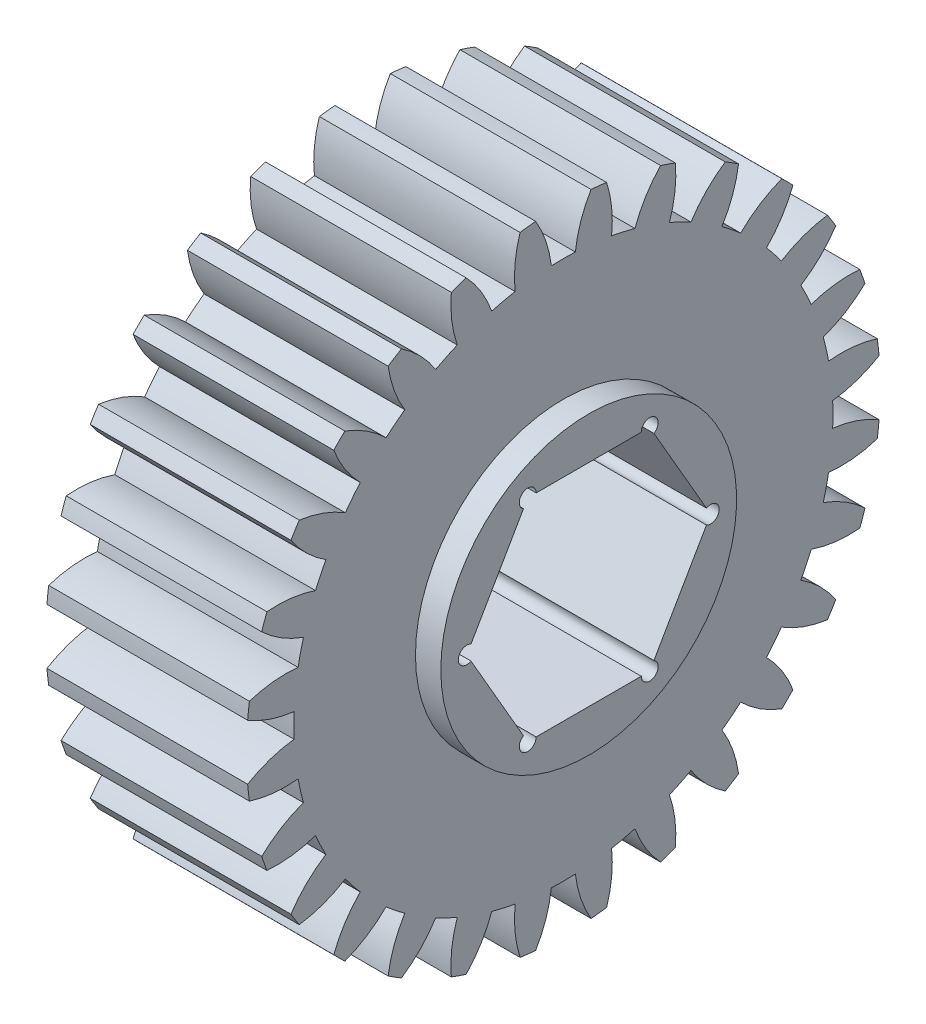
SolidWorks part; units mm, degrees
ref_plane "Plane1" through (0, 0, 0) normal (0, 0, 1) x (1, 0, 0)
ref_plane "Plane2" through (0, 0, 0) normal (0, 1, 0) x (1, 0, 0)
ref_plane "Plane3" through (0, 0, 0) normal (1, 0, 0) x (0, 0, -1)
sketch "HoldingSke" plane through (0, 0, 0) normal (0, 1, 0) x (1, 0, 0)
  line L0 (0, 0) -> (448.5374, -238.4916)
  line L1 (-15, 0) -> (100, 0) construction
  line L2 (0, 0) -> (-2.1039, 2.3779)
  line L3 (0, 0) -> (-11.863, 4.5341)
  line L4 (0, 0) -> (7.6251, 4.0544)
  line L5 (0, 0) -> (-47.5972, -17.7524)
  line L6 (0, 0) -> (-10.0014, -6.748)
  line L7 (-2.1039, 2.3779) -> (8.8308, 51.9871)
  line L8 (-76.2, 54.61) -> (-72.771, 54.61)
  line L9 (-67.7845, 28.3722) -> (-49.3413, 33.142)
  line L10 (-76.2, 71.12) -> (104.1128, 71.12)
  line L11 (0, 0) -> (-12.065, 0)
  line L12 (-76.2, 101.6) -> (-76.1492, 101.6)
  line L13 (24.9733, 27.94) -> (52.9518, 28.4284)
  line L14 (24.9733, 27.94) -> (25.0241, 27.9398)
  line L15 (24.9733, 27.94) -> (100.4021, 29.52)
  circle A0 centre (0, 0) radius 1.5875
  circle A1 centre (0, 0) radius 16.2052
  circle A2 centre (0, 0) radius 38.1
  circle A3 centre (0, 0) radius 1.5875
  dimension "MHD" = 32.4104
  dimension "Hub_dia" = 76.2
  dimension "Bore" = 3.175
  dimension "MBD" = 3.175
  dimension "Num_teeth" = 28
  dimension "Pitch" = 508
  dimension "Overall_len" = 50.8
  dimension "Show_teeth" = 28
  dimension "Thickness" = 12.065
  dimension "OAL" = 50.8001
  dimension "T_dim" = 3.429
  dimension "Ap" = 14.5
  dimension "H" = 19.05
  dimension "Pitch_radius" = 180.3128
  dimension "Width" = 12.065
  dimension "Backlash" = 0.0508
  dimension "Addendum_fac" = 1
  dimension "Dedendum_fac" = 1.2
  dimension "Clearance_fac" = 0.2
  dimension "Dedendum_add" = 0.0508
sketch "BasProSke" plane through (0, 0, 0) normal (0, 1, 0) x (1, 0, 0)
  line L0 (-10, 0) -> (60, 0) construction
  line L1 (0, 0) -> (0, 19.05)
  line L2 (0, 0) -> (12.065, 0)
  line L3 (12.065, 0) -> (12.065, 19.05)
  line L4 (12.065, 19.05) -> (0, 19.05)
  dimension "Thickness" = 12.065
  dimension "Diameter" = 38.1
revolve "Base-Revolve" add sketch "BasProSke" angle 360 about L0
sketch "TooCutSke" plane through (0, 0, 0) normal (1, 0, 0) x (0, 0, -1)
  line L1 (0, 0) -> (0, 107) construction
  line L2 (0, 0) -> (-1.0858, 17.7468) construction
  line L3 (0, 0) -> (-3.9763, 35.2903) construction
  line L4 (-1.0858, 17.7468) -> (-1.9881, 17.6451) construction
  arc A0 (0.7203, 16.1892) -> (-0.7203, 16.1892) centre (0, 0) ccw
  arc A1 (1.6778, 19.0015) -> (-1.6778, 19.0015) centre (0, 0) ccw
  circle A2 centre (0, 0) radius 17.78 construction
  circle A3 centre (0, 0) radius 17.2137 construction
  arc A4 (-0.7203, 16.1892) -> (-1.6778, 19.0015) centre (-7.7831, 15.3536) ccw
  arc A5 (1.6778, 19.0015) -> (0.7203, 16.1892) centre (7.7831, 15.3536) ccw
  dimension "Root_dia" = 32.4104
  dimension "Overcut_dia" = 38.1508
  dimension "Pitch_dia" = 35.56
  dimension "Base_dia" = 34.4273
  dimension "Flank_rad" = 7.112
  dimension "Half_ang" = 6.429
  dimension "Half_CT" = 0.908
extrude "ToothCut" cut sketch "TooCutSke" along normal through all
fillet "Breaks" [suppressed] radius 0.0254
fillet "RootFillets" [suppressed] radius 0.3048
pattern_circular "TeethCuts" count 28 every 12.857 about axis through (-10, 0, 0) along (1, 0, 0) of "ToothCut", "RootFillets", "Breaks"
sketch "HubNeaOneSke" plane through (0, 0, 0) normal (-1, 0, 0) x (0, 0, 1)
  circle A0 centre (0, 0) radius 16.2052
  dimension "Diameter" = 32.4104
extrude "HubNearOne" [suppressed] add sketch "HubNeaOneSke" along normal blind 38.7351
sketch "HubNeaBotSke" plane through (0, 0, 0) normal (-1, 0, 0) x (0, 0, 1)
  circle A0 centre (0, 0) radius 16.2052
  dimension "Diameter" = 32.4104
extrude "HubNearBoth" [suppressed] add sketch "HubNeaBotSke" along normal blind 19.3675
ref_plane "FarPln" through (12.065, 0, 0) normal (1, 0, 0) x (0, 0, -1)
sketch "HubFarSke" plane through (12.065, 0, 0) normal (1, 0, 0) x (0, 0, -1)
  circle A0 centre (0, 0) radius 16.2052
  dimension "Diameter" = 32.4104
extrude "HubFar" [suppressed] add sketch "HubFarSke" along normal blind 19.3675
sketch "BorSke" plane through (0, 0, 0) normal (1, 0, 0) x (0, 0, -1)
  circle A0 centre (0, 0) radius 1.5875
  dimension "Diameter" = 3.175
extrude "Bore" cut sketch "BorSke" along normal mid plane 101.6001
sketch "KeySke" plane through (0, 0, 0) normal (1, 0, 0) x (0, 0, -1)
  line L0 (-0.127, 0) -> (-0.127, 1.8415)
  line L1 (-0.127, 1.8415) -> (0.127, 1.8415)
  line L2 (0.127, 1.8415) -> (0.127, 0)
  line L3 (0, 0) -> (0, 34) construction
  line L4 (-0.127, 0) -> (0.127, 0)
  dimension "Offset" = 1.8415
  dimension "Width" = 0.254
extrude "Keyway" [suppressed] cut sketch "KeySke" along normal mid plane 101.6001
pattern_circular "Keyway2" [suppressed] count 2 every 90 about axis through (-10, 0, 0) along (1, 0, 0)
sketch "Sketch1" plane through (12.065, 0, 0) normal (1, 0, 0) x (0, 0, -1)
  circle A0 centre (0, 0) radius 8.89
  dimension "D1" = 17.78
extrude "Boss-Extrude1" add sketch "Sketch1" along normal blind 1.524
sketch "Sketch2" plane through (13.589, 0, 0) normal (1, 0, 0) x (0, 0, -1)
  line L1 (7.3323, 0) -> (3.6662, 6.35)
  line L2 (3.6662, 6.35) -> (-3.6662, 6.35)
  line L3 (-3.6662, 6.35) -> (-7.3323, 0)
  line L4 (-7.3323, 0) -> (-3.6662, -6.35)
  line L5 (-3.6662, -6.35) -> (3.6662, -6.35)
  line L6 (3.6662, -6.35) -> (7.3323, 0)
  circle A0 centre (0, 0) radius 6.35 construction
  circle A1 centre (-3.6662, 6.35) radius 0.508
  circle A2 centre (3.6662, 6.35) radius 0.508
  circle A3 centre (7.3323, 0) radius 0.508
  circle A4 centre (3.6662, -6.35) radius 0.508
  circle A5 centre (-3.6662, -6.35) radius 0.508
  circle A6 centre (-7.3323, 0) radius 0.508
  dimension "D1" = 12.7
  dimension "D2" = 1.016
extrude "Cut-Extrude1" cut sketch "Sketch2" against normal through all contours L4 A6 L3 | L3 A6 L4 | A6 L4 A5 L5 A4 L6 A3 L1 A2 L2 A1 L3 | L2 A1 L3 | L3 A1 L2 | L2 A2 L1 | L1 A3 L6 | L6 A4 L5
equation "' \"Pitch@HoldingSke\" = 4"
equation "' \"Num_teeth@HoldingSke\" = 12"
equation "' \"Ap@HoldingSke\" =  20"
equation "' \"Ap@HoldingSke\" = 20"
equation "' \"Width@HoldingSke\" = 0.5"
equation "' \"Hub_dia@HoldingSke\"= 1"
equation "' \"Hub_dia@HoldingSke\" = 1"
equation "' \"Overall_len@HoldingSke\" = 1.0"
equation "' \"Bore@HoldingSke\" = 0.75"
equation "' \"T_dim@HoldingSke\" = 0.85"
equation "' \"Width@KeySke\" = 0.25"
equation "' \"Show_teeth@HoldingSke\" = 13"
equation "' \"Backlash@HoldingSke\" = 0.009"
equation "' \"Addendum_fac@HoldingSke\" = 1.0"
equation "' \"Dedendum_fac@HoldingSke\" = 1.25"
equation "' \"Dedendum_add@HoldingSke\" = 0.00005"
equation "' \"Clearance_fac@HoldingSke\" = 0.25"
equation "' \"Pitch@HoldingSke\" = 0.5"
equation "' \"Num_teeth@HoldingSke\" = 23"
equation "' \"Show_teeth@HoldingSke\" = 23"
equation "' \"Backlash@HoldingSke\" = 0.0375"
equation "\"Overcut_dia@TooCutSke\" = (\"Num_teeth@HoldingSke\" + 2 * \"Addendum_fac@HoldingSke\") / \"Pitch@HoldingSke\" + 0.002"
equation "\"Pitch_dia@TooCutSke\" = \"Num_teeth@HoldingSke\" / \"Pitch@HoldingSke\""
equation "\"Base_dia@TooCutSke\" = \"Num_teeth@HoldingSke\" / \"Pitch@HoldingSke\" * cos((\"Ap@HoldingSke\"  * 3.14159265 / 180))"
equation "\"Root_dia@TooCutSke\" = (\"Num_teeth@HoldingSke\" + 2) / \"Pitch@HoldingSke\" - 2 * (\"Addendum_fac@HoldingSke\" + \"Dedendum_fac@HoldingSke\") / \"Pitch@HoldingSke\" - \"Dedendum_add@HoldingSke\" * 2"
equation "\"Half_ang@TooCutSke\" = 180 / \"Num_teeth@HoldingSke\""
equation "\"Half_CT@TooCutSke\" = \"Num_teeth@HoldingSke\" / \"Pitch@HoldingSke\" * sin((3.14159265 / 2 / \"Num_teeth@HoldingSke\")) / 2 - 7 * \"Backlash@HoldingSke\" / 4"
equation "\"Flank_rad@TooCutSke\" = \"Num_teeth@HoldingSke\" / \"Pitch@HoldingSke\" / 5"
equation "\"Radius@RootFillets\" = \"Clearance_fac@HoldingSke\" / \"Pitch@HoldingSke\" + \"Dedendum_add@HoldingSke\""
equation "\"Break_rad@Breaks\" = 0.02 / \"Pitch@HoldingSke\""
equation "\"Thickness@HoldingSke\" = \"Width@HoldingSke\""
equation "\"OAL@HoldingSke\" = \"Thickness@HoldingSke\""
equation "\"MHD@HoldingSke\" = (\"Num_teeth@HoldingSke\" + 2) / \"Pitch@HoldingSke\" - 2 * (\"Addendum_fac@HoldingSke\" + \"Dedendum_fac@HoldingSke\")  / \"Pitch@HoldingSke\" - \"Dedendum_add@HoldingSke\" * 2"
equation "\"MBD@HoldingSke\" = (\"Num_teeth@HoldingSke\" + 2) / \"Pitch@HoldingSke\" - 2 * (\"Addendum_fac@HoldingSke\" + \"Dedendum_fac@HoldingSke\")  / \"Pitch@HoldingSke\" - \"Dedendum_add@HoldingSke\" * 2 - 0.002"
equation "\"MHD@HoldingSke\" = ((sgn( \"MHD@HoldingSke\" - \"Hub_dia@HoldingSke\" )-1)*( \"MHD@HoldingSke\" - \"Hub_dia@HoldingSke\" ))/-2+ \"Hub_dia@HoldingSke\""
equation "\"MBD@HoldingSke\" = ((sgn( \"MBD@HoldingSke\" - \"Bore@HoldingSke\" )-1)*( \"MBD@HoldingSke\" - \"Bore@HoldingSke\" ))/-2+ \"Bore@HoldingSke\""
equation "\"OAL@HoldingSke\" = ((sgn( \"OAL@HoldingSke\" - \"Overall_len@HoldingSke\" )+1)*( \"OAL@HoldingSke\" - \"Overall_len@HoldingSke\" ))/2 + \"Overall_len@HoldingSke\" + 0.000002"
equation "\"Num_teeth@TeethCuts\" = int( \"Show_teeth@HoldingSke\" ) + 1"
equation "\"Num_teeth@TeethCuts\" = ((sgn( \"Num_teeth@TeethCuts\" - \"Num_teeth@HoldingSke\" )-1)*( \"Num_teeth@TeethCuts\" - \"Num_teeth@HoldingSke\" ))/-2+ \"Num_teeth@HoldingSke\""
equation "\"Num_teeth@TeethCuts\" = ((sgn( \"Num_teeth@TeethCuts\" - 2.0)+1)*( \"Num_teeth@TeethCuts\" - 2.0))/2 +2.0"
equation "\"Angle@TeethCuts\" = 360.0 / \"Num_teeth@HoldingSke\""
equation "\"Diameter@BasProSke\" = (\"Num_teeth@HoldingSke\" + 2 * \"Addendum_fac@HoldingSke\") / \"Pitch@HoldingSke\""
equation "\"Thickness@BasProSke\"  = \"Thickness@HoldingSke\""
equation "' \"Fillet_rad@BasProSke\" =  \"Thickness@HoldingSke\" * 0.05"
equation "' \"Fillet_rad@BasProSke\" = \"Thickness@HoldingSke\" * 0.05"
equation "\"MHD@HoldingSke\" = ((sgn( \"MHD@HoldingSke\" - \"Root_dia@TooCutSke\" )-1)*( \"MHD@HoldingSke\" - \"Root_dia@TooCutSke\" ))/-2+ \"Root_dia@TooCutSke\""
equation "\"Diameter@HubNeaOneSke\" = \"MHD@HoldingSke\""
equation "\"Length@HubNearOne\" = \"OAL@HoldingSke\" - \"Thickness@BasProSke\""
equation "\"Diameter@HubNeaBotSke\" = \"MHD@HoldingSke\""
equation "\"Length@HubNearBoth\" = ( \"OAL@HoldingSke\" - \"Thickness@BasProSke\" ) / 2.0"
equation "\"Thickness@FarPln\" = \"Thickness@BasProSke\""
equation "\"Diameter@HubFarSke\" = \"MHD@HoldingSke\""
equation "\"Length@HubFar\" = ( \"OAL@HoldingSke\" - \"Thickness@BasProSke\" ) / 2.0"
equation "\"Diameter@BorSke\" = \"MBD@HoldingSke\""
equation "\"D1@Bore\" = \"OAL@HoldingSke\" * 2.0"
equation "\"D1@Keyway\" = \"OAL@HoldingSke\" * 2.0"
equation "\"Offset@KeySke\" = \"T_dim@HoldingSke\" - \"MBD@HoldingSke\" / 2.0"
